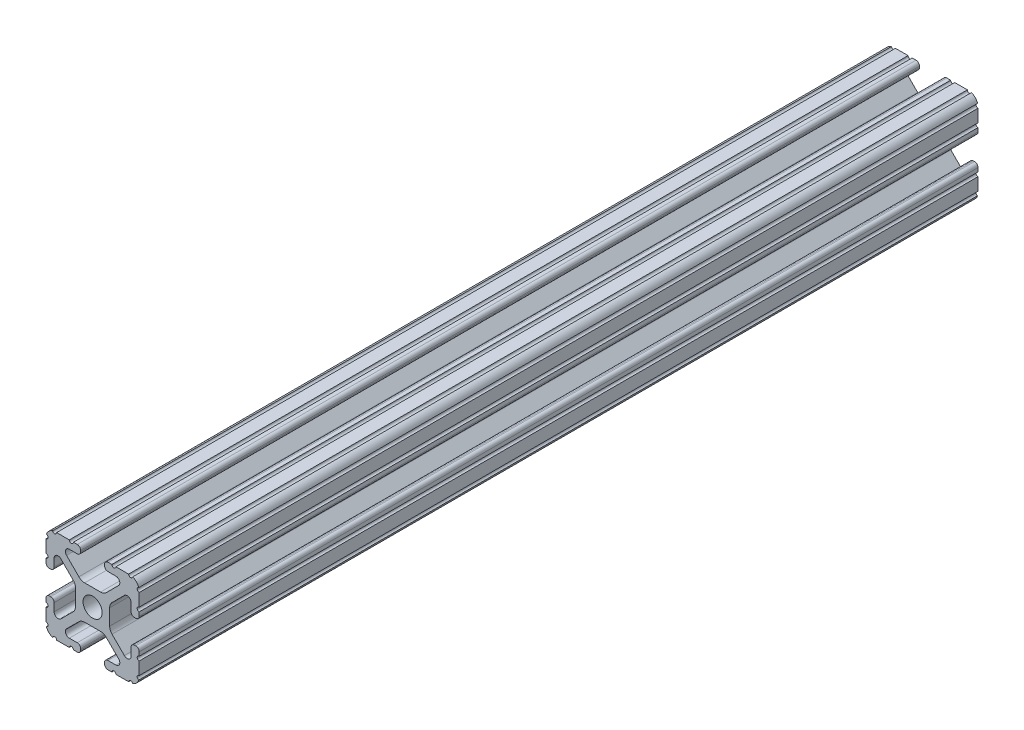
SolidWorks part; units mm, degrees
material "6061-T6 (SS)"
ref_plane "Front Plane" through (0, 0, 0) normal (0, 0, 1) x (1, 0, 0)
ref_plane "Top Plane" through (0, 0, 0) normal (0, 1, 0) x (1, 0, 0)
ref_plane "Right Plane" through (0, 0, 0) normal (1, 0, 0) x (0, 0, -1)
sketch "Sketch2" plane through (0, 0, 0) normal (0, 0, 1) x (1, 0, 0)
  line L0 (0, 12.7) -> (0, -12.7) construction
  line L1 (-12.7, 0) -> (12.7, 0) construction
  line L2 (3.2512, -12.7) -> (12.7, -12.7)
  line L3 (12.7, -12.7) -> (12.7, -3.2512)
  line L4 (3.2512, -12.7) -> (3.2512, -10.4902)
  line L5 (3.2512, -10.4902) -> (8.9276, -10.4902)
  line L6 (8.9276, -10.4902) -> (3.0856, -4.6482)
  line L7 (0, 0) -> (12.7, -12.7) construction
  line L8 (12.7, -3.2512) -> (10.4902, -3.2512)
  line L9 (10.4902, -3.2512) -> (10.4902, -8.9276)
  line L10 (10.4902, -8.9276) -> (4.6482, -3.0856)
  circle A0 centre (0, 0) radius 2.6035
  arc A1 (6.3485, -10.4902) -> (7.1039, -8.6665) centre (6.3485, -9.4219) ccw construction
  point P8 (0, -4.6482)
  dimension "Center Hole Diameter" = 5.207
  dimension "Rail Height" = 25.4
  dimension "Rail Width" = 25.4
  dimension "T-Slot Width" = 6.5024
  dimension "Slot Inner Width" = 14.8336
  dimension "Thickness" = 2.2098
  dimension "Slot Depth" = 5.842
  dimension "D1" = 2.2098
sketch "Sketch3" plane through (0, 0, 0) normal (1, 0, 0) x (0, 0, -1)
  line L0 (-152.4, -12.7) -> (152.4, -12.7) construction
  line L1 (-127, 0) -> (127, 0) construction
  dimension "D1" = 25.4
  dimension "Length" = 304.8
sketch "Sketch4" plane through (0, 0, 0) normal (0, 0, 1) x (1, 0, 0)
  line L0 (4.1904, -12.7) -> (10.1173, -12.7)
  line L1 (3.2512, -12.7) -> (12.7, -12.7) construction
  line L2 (3.2512, -12.7) -> (3.2512, -10.4902) construction
  line L3 (3.2512, -10.4902) -> (8.9276, -10.4902) construction
  line L4 (3.2512, -11.4294) -> (3.2512, -11.7608)
  line L5 (4.1904, -10.4902) -> (6.3485, -10.4902)
  line L6 (0, -4.6482) -> (2.164, -4.6482)
  line L7 (8.9276, -10.4902) -> (3.0856, -4.6482) construction
  line L8 (3.7373, -5.2999) -> (7.1039, -8.6665)
  line L9 (12.7, -12.7) -> (12.7, -3.2512) construction
  line L10 (10.4902, -8.9276) -> (4.6482, -3.0856) construction
  line L11 (10.4902, -3.2512) -> (10.4902, -8.9276) construction
  line L12 (10.4902, -6.3485) -> (10.4902, -4.1904)
  line L13 (12.7, -3.2512) -> (10.4902, -3.2512) construction
  line L14 (11.4294, -3.2512) -> (11.7608, -3.2512)
  line L15 (12.7, -4.1904) -> (12.7, -10.1173)
  line L16 (8.6665, -7.1039) -> (5.2999, -3.7373)
  line L17 (4.6482, 0) -> (4.6482, -2.164)
  line L18 (-12.7, 0) -> (12.7, 0) construction
  line L19 (0, -4.6482) -> (0, -2.6035)
  line L20 (0, 12.7) -> (0, -12.7) construction
  line L21 (4.6482, 0) -> (2.6035, 0)
  arc A0 (3.2512, -11.7608) -> (4.1904, -12.7) centre (4.1904, -11.7608) ccw
  arc A2 (3.2512, -11.4294) -> (4.1904, -10.4902) centre (4.1904, -11.4294) cw
  arc A3 (6.3485, -10.4902) -> (7.1039, -8.6665) centre (6.3485, -9.4219) ccw
  arc A4 (2.164, -4.6482) -> (3.7373, -5.2999) centre (2.164, -6.8732) cw
  arc A5 (10.1173, -12.7) -> (12.7, -10.1173) centre (10.1173, -10.1173) ccw
  arc A6 (8.6665, -7.1039) -> (10.4902, -6.3485) centre (9.4219, -6.3485) ccw
  arc A7 (10.4902, -4.1904) -> (11.4294, -3.2512) centre (11.4294, -4.1904) cw
  arc A8 (11.7608, -3.2512) -> (12.7, -4.1904) centre (11.7608, -4.1904) cw
  arc A9 (5.2999, -3.7373) -> (4.6482, -2.164) centre (6.8732, -2.164) cw
  circle A10 centre (0, 0) radius 2.6035 construction
  arc A11 (0, -2.6035) -> (2.6035, 0) centre (0, 0) ccw
  dimension "D1" = 2.5827
  dimension "D2" = 2.225
  dimension "D3" = 0.9392
extrude "Boss-Extrude1" add sketch "Sketch4" along normal mid plane 228.6
sketch "Sketch5" plane through (0, 0, 0) normal (0, 0, 1) x (1, 0, 0)
  line L0 (3.2512, -12.7) -> (12.7, -12.7) construction
  line L1 (4.1904, -10.4902) -> (6.3485, -10.4902) construction
  line L3 (0, 0) -> (12.7, -12.7) construction
  line L4 (6.3485, -10.4902) -> (6.3485, -12.7) construction
  line L5 (8.9276, -10.4902) -> (3.0856, -4.6482) construction
  circle A0 centre (10.3562, -12.7) radius 0.5524
  circle A1 centre (5.796, -12.7) radius 0.5524
  circle A2 centre (12.7, -10.3562) radius 0.5524
  circle A3 centre (12.7, -5.796) radius 0.5524
  point P10 (5.2694, -10.4902)
  point P12 (9.4219, -6.3485)
  dimension "D1" = 1.1049
extrude "Cut-Extrude1" cut sketch "Sketch5" against normal through all both and the other way through all
mirror "Mirror1" about plane through (0, 0, 0) normal (1, 0, 0) of bodies 137 134
mirror "Mirror2" about plane through (0, 0, 0) normal (0, 1, 0) of bodies 135
equation "\"D1@Boss-Extrude1\"=9"
equation "\"D1@Sketch2\"= \"Thickness@Sketch2\""
equation "\"D2@Sketch4\"=\"Slot Inner Width@Sketch2\"*0.15"
equation "\"D1@Sketch4\"=\"D3@Sketch4\"*2.75"
equation "\"D3@Sketch4\"=\"Thickness@Sketch2\"*0.425"
equation "\"D1@Sketch5\"=\"Thickness@Sketch2\"*0.5"
